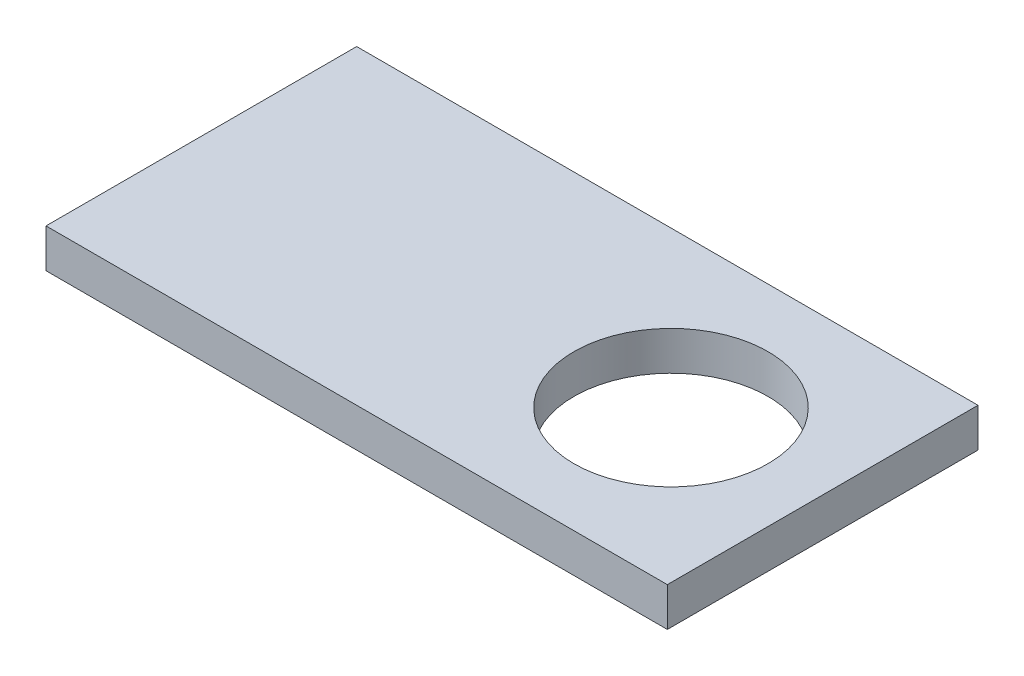
SolidWorks part; units mm, degrees
ref_plane "Front Plane" through (0, 0, 0) normal (0, 0, 1) x (1, 0, 0)
ref_plane "Top Plane" through (0, 0, 0) normal (0, 1, 0) x (1, 0, 0)
ref_plane "Right Plane" through (0, 0, 0) normal (1, 0, 0) x (0, 0, -1)
sketch "Sketch1" plane through (0, 0, 0) normal (0, 1, 0) x (1, 0, 0)
  line L0 (0, 0) -> (0, 20.32)
  line L1 (0, 20.32) -> (40.64, 20.32)
  line L2 (40.64, 20.32) -> (40.64, 0)
  line L3 (40.64, 0) -> (0, 0)
  circle A0 centre (30.734, 10.144) radius 6.35
  dimension "D3" = 12.7
  dimension "D4" = 9.906
  dimension "D1" = 20.32
  dimension "D2" = 40.64
extrude "Boss-Extrude1" add sketch "Sketch1" along normal blind 2.54
